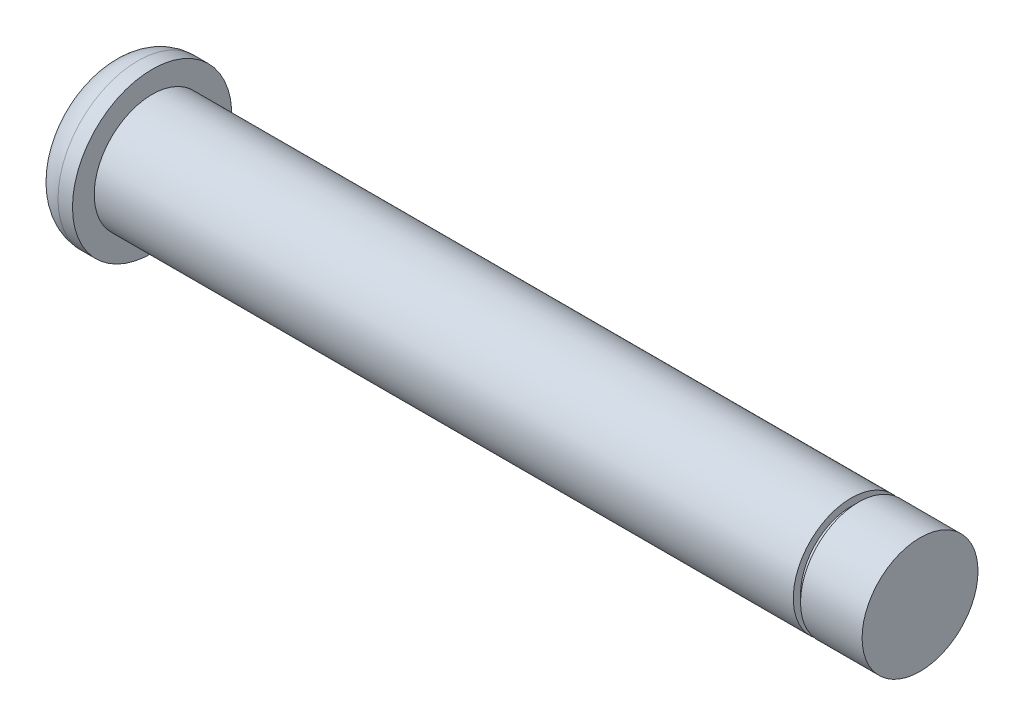
SolidWorks part; units mm, degrees
ref_plane "Front Plane" through (0, 0, 0) normal (0, 0, 1) x (1, 0, 0)
ref_plane "Top Plane" through (0, 0, 0) normal (0, 1, 0) x (1, 0, 0)
ref_plane "Right Plane" through (0, 0, 0) normal (1, 0, 0) x (0, 0, -1)
sketch "Sketch1" plane through (0, 0, 0) normal (1, 0, 0) x (0, 0, -1)
  circle A0 centre (0, 0) radius 4
  dimension "D1" = 8
extrude "Boss-Extrude1" add sketch "Sketch1" along normal blind 53
sketch "Sketch2" plane through (0, 0, 0) normal (-1, 0, 0) x (0, 0, 1)
  circle A0 centre (0, 0) radius 5.5
  dimension "D1" = 11
extrude "Boss-Extrude2" add sketch "Sketch2" along normal blind 3
fillet "Fillet1" radius 2 1 edges at (-3, 0, 5.5)
sketch "Sketch4" plane through (0, 0, 0) normal (0, 0, 1) x (1, 0, 0)
  line L0 (53, 4) -> (0, 4) construction
  line L1 (48.25, 4.5) -> (48.75, 4.5)
  line L2 (48.25, 4.5) -> (48.25, 3.5)
  line L3 (48.25, 3.5) -> (48.75, 3.5)
  line L4 (48.75, 4.5) -> (48.75, 3.5)
  line L5 (48.25, 4.5) -> (48.75, 3.5) construction
  line L6 (48.25, 3.5) -> (48.75, 4.5) construction
  line L7 (0, 0) -> (53.351, 0) construction
  point P0 (48.5, 4)
  dimension "D1" = 0.5
  dimension "D2" = 1
  dimension "D3" = 48.5
revolve "Cut-Revolve1" cut sketch "Sketch4" angle 360 about L7
